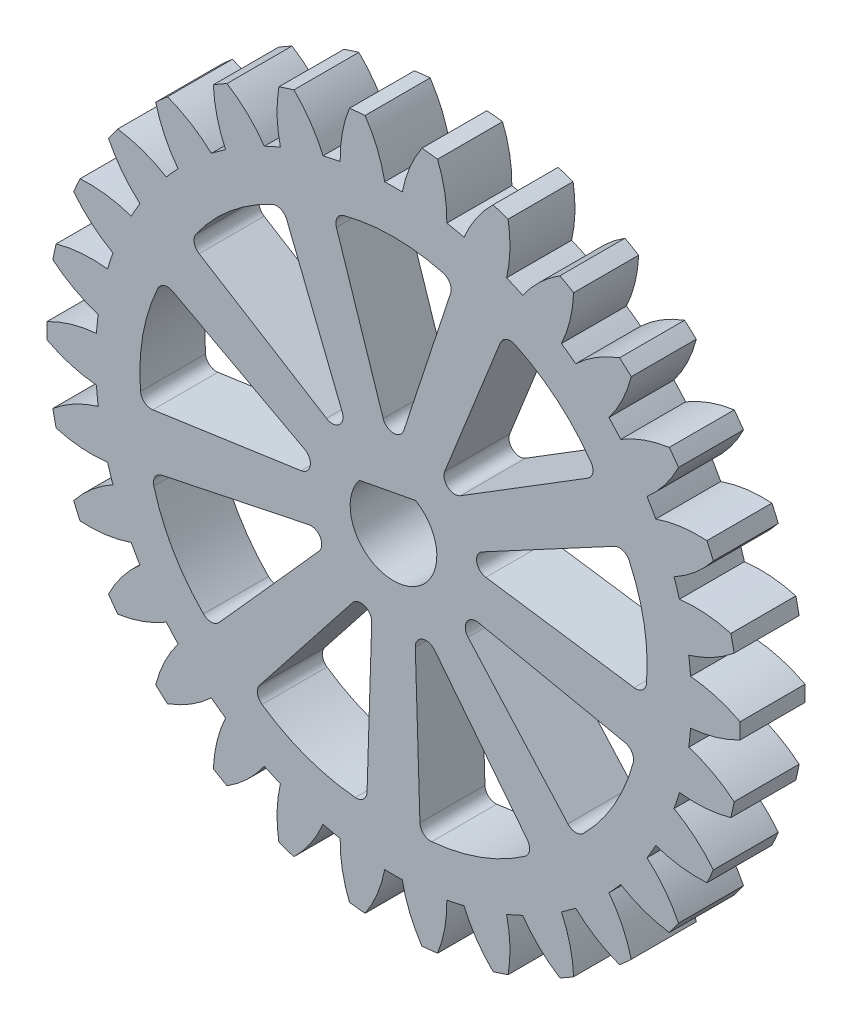
SolidWorks part; units mm, degrees
ref_plane "Front Plane" through (0, 0, 0) normal (0, 0, 1) x (1, 0, 0)
ref_plane "Top Plane" through (0, 0, 0) normal (0, 1, 0) x (1, 0, 0)
ref_plane "Right Plane" through (0, 0, 0) normal (1, 0, 0) x (0, 0, -1)
sketch "Sketch1" plane through (0, 0, 0) normal (0, 0, 1) x (1, 0, 0)
  circle A0 centre (0, 0) radius 16
extrude "Boss-Extrude2" add sketch "Sketch1" along normal blind 3
sketch "Sketch7" plane through (0, 0, 3) normal (0, 0, 1) x (1, 0, 0)
  line L0 (0, 0) -> (0, 27.6236) construction
  line L1 (0, 0) -> (-2.0601, 19.6004) construction
  line L2 (-0.7847, 14.9795) -> (-1.5658, 14.8974) construction
  circle A0 centre (0, 0) radius 14.0954 construction
  circle A1 centre (0, 0) radius 13.75 construction
  circle A2 centre (0, 0) radius 15 construction
  arc A3 (-1.31, 15.9463) -> (-0.4053, 13.744) centre (-6.2972, 12.6105) cw
  arc A4 (1.31, 15.9463) -> (0.4053, 13.744) centre (6.2972, 12.6105) ccw
  arc A5 (1.31, 15.9463) -> (-1.31, 15.9463) centre (0, 0) ccw
  circle A6 centre (0, 0) radius 16 construction
  arc A7 (-0.4053, 13.744) -> (0.4053, 13.744) centre (0, 0) cw
  dimension "D5" = 0.7854
extrude "Cut-Extrude4" cut sketch "Sketch7" against normal through all
pattern_circular "CirPattern3" count 30 over 360 about axis through (0, 0, 0) along (0, 0, 1) of "Cut-Extrude4"
sketch "Sketch8" [suppressed] plane through (0, 0, 0) normal (0, 0, -1) x (-1, 0, 0)
  line L7 (0, 0) -> (0, 20.625) construction
  line L8 (10, 13.7477) -> (0, 3.7477)
  line L9 (-10, 13.7477) -> (0, 3.7477)
  arc A1 (0.6079, 20.616) -> (-0.6079, 20.616) centre (0, 0) ccw construction
  arc A3 (10, 13.7477) -> (-10, 13.7477) centre (0, 0) ccw
  dimension "D1" = 10
  dimension "D3" = 90
  dimension "D2" = 17
extrude "Cut-Extrude5" [suppressed] cut sketch "Sketch8" against normal through all
fillet "Fillet2" [suppressed] radius 2
fillet "Fillet3" [suppressed] radius 2
fillet "Fillet4" [suppressed] radius 2
pattern_circular "CirPattern5" [suppressed] count 4 over 360
sketch "Sketch9" plane through (0, 0, 0) normal (0, 0, -1) x (-1, 0, 0)
  line L0 (0, 0) -> (0, 13.75) construction
  line L1 (-2.7976, 11.3018) -> (0, 2.8018)
  line L2 (2.7976, 11.3018) -> (0, 2.8018)
  arc A0 (0.4053, 13.744) -> (-0.4053, 13.744) centre (0, 0) ccw construction
  arc A1 (-2.7976, 11.3018) -> (2.7976, 11.3018) centre (0, 2.8018) cw
  dimension "D2" = 8.9485
  dimension "D1" = 8.5
  dimension "D3" = 8.5
  dimension "D4" = 2.8018
extrude "Cut-Extrude6" cut sketch "Sketch9" against normal through all
fillet "Fillet6" radius 0.5 3 edges at (0, 2.8018, 1.5) (2.7976, 11.3018, 1.5) (-2.7976, 11.3018, 1.5)
pattern_circular "CirPattern6" count 9 over 360 about axis through (0, 0, 0) along (0, 0, 1) of "Cut-Extrude6", "Fillet6"
sketch "Sketch10" plane through (0, 0, 0) normal (0, 0, -1) x (-1, 0, 0)
  line L0 (-1.0197, 1.7205) -> (1.5796, 1.2268)
  arc A0 (-1.0197, 1.7205) -> (1.5796, 1.2268) centre (0, 0) ccw
  dimension "D1" = 1.5
  dimension "D2" = 2
  dimension "D3" = 2.5993
extrude "Cut-Extrude7" cut sketch "Sketch10" against normal through all
equation "\"module\"= 1.0"
equation "\"teeth\" = 30"
equation "\"pressureAngle\"= 20deg"
equation "\"gearThickness\"= 3"
equation "\"addendumFactor\"= 1"
equation "\"dedendumFactor\"= 1.25"
equation "\"pitch\"= 1 / \"module\""
equation "\"pitchDiameter\"= \"teeth\" / \"pitch\""
equation "\"addendum\"= \"addendumFactor\" / \"pitch\""
equation "\"dedendum\"= \"dedendumFactor\" / \"pitch\""
equation "\"D1@Sketch1\"=\"pitchDiameter\" +2 * \"addendum\""
equation "\"D1@Boss-Extrude2\"=\"gearThickness\""
equation "\"D1@Sketch7\"=\"pitchDiameter\" -2 * \"dedendum\""
equation "\"D2@Sketch7\"=\"pitchDiameter\" * cos(\"pressureAngle\")"
equation "\"D3@Sketch7\"=\"pitchDiameter\""
equation "\"addendumDiameter@Sketch7\" = 180 / \"teeth\""
equation "\"D4@Sketch7\"=\"pitchDiameter\"/5"
equation "\"D5@Sketch7\"=PI/2/\"pitch\"/2"
equation "\"D1@CirPattern3\"=\"teeth\""
